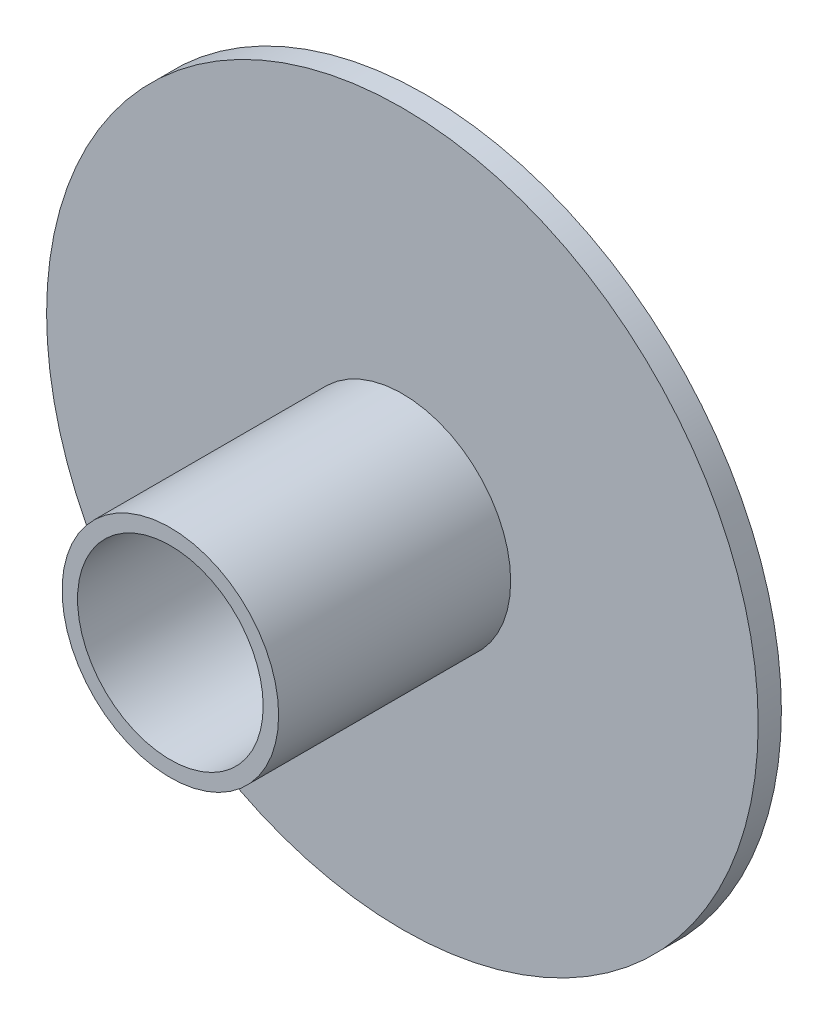
SolidWorks part; units mm, degrees
ref_plane "Front" through (0, 0, 0) normal (0, 0, 1) x (1, 0, 0)
ref_plane "Top" through (0, 0, 0) normal (0, 1, 0) x (1, 0, 0)
ref_plane "Right" through (0, 0, 0) normal (1, 0, 0) x (0, 0, -1)
sketch "Sketch1" plane through (0, 0, 0) normal (0, 0, 1) x (1, 0, 0)
  circle A0 centre (0, 0) radius 21.5 construction
  circle A1 centre (0, 0) radius 23
  dimension "D1" = 43
  dimension "D2" = 1.5
extrude "Boss-Extrude1" add sketch "Sketch1" along normal blind 1.5 contours A1
sketch "Sketch2" plane through (0, 0, 1.5) normal (0, 0, 1) x (1, 0, 0)
  circle A0 centre (0, 0) radius 6 construction
  circle A1 centre (0, 0) radius 7
  dimension "D1" = 12
  dimension "D2" = 1
extrude "Boss-Extrude2" add sketch "Sketch2" along normal blind 15
sketch "Sketch3" plane through (0, 0, 16.5) normal (0, 0, 1) x (1, 0, 0)
  circle A0 centre (0, 0) radius 6
  dimension "D1" = 12
extrude "Cut-Extrude1" cut sketch "Sketch3" against normal through all both and the other way through all contours A0
equation "\"D1@Sketch1\"=\"Cavity_Diameter\""
equation "\"Wall_Thickness\"= 1.5"
equation "\"Cavity_Diameter\"= 43"
equation "\"D2@Sketch1\"=\"Wall_Thickness\""
equation "\"D1@Boss-Extrude1\"=\"Wall_Thickness\""
equation "\"Outlet_Diameter\"= 12"
equation "\"D1@Sketch2\"=\"Outlet_Diameter\""
equation "\"Outlet_Length\"= 15"
equation "\"D1@Boss-Extrude2\"=\"Outlet_Length\""
equation "\"D1@Sketch3\"=\"Outlet_Diameter\""
